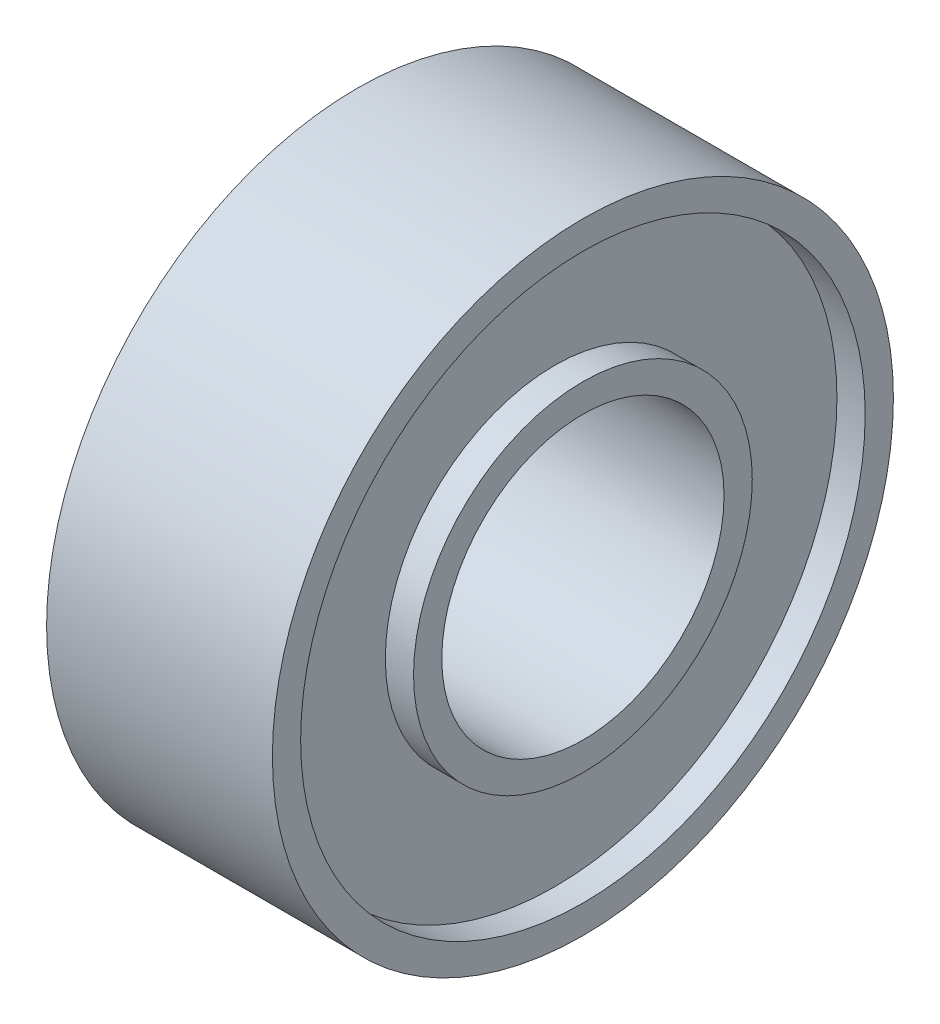
SolidWorks part; units mm, degrees
ref_plane "Front Plane" through (0, 0, 0) normal (0, 0, 1) x (1, 0, 0)
ref_plane "Top Plane" through (0, 0, 0) normal (0, 1, 0) x (1, 0, 0)
ref_plane "Right Plane" through (0, 0, 0) normal (1, 0, 0) x (0, 0, -1)
sketch "Sketch1" plane through (0, 0, 0) normal (1, 0, 0) x (0, 0, -1)
  circle A0 centre (0, 0) radius 5.5
  circle A1 centre (0, 0) radius 2.5
  dimension "D1" = 11
  dimension "D2" = 5
extrude "Boss-Extrude1" add sketch "Sketch1" along normal blind 4
sketch "Sketch2" plane through (4, 0, 0) normal (1, 0, 0) x (0, 0, -1)
  circle A0 centre (0, 0) radius 3
  circle A1 centre (0, 0) radius 5
  dimension "D1" = 6
  dimension "D2" = 10
extrude "Cut-Extrude1" cut sketch "Sketch2" against normal blind 0.5
sketch "Sketch3" plane through (0, 0, 0) normal (-1, 0, 0) x (0, 0, 1)
  circle A0 centre (0, 0) radius 3
  circle A1 centre (0, 0) radius 5
  dimension "D1" = 6
  dimension "D2" = 10
extrude "Cut-Extrude2" cut sketch "Sketch3" against normal blind 0.5
